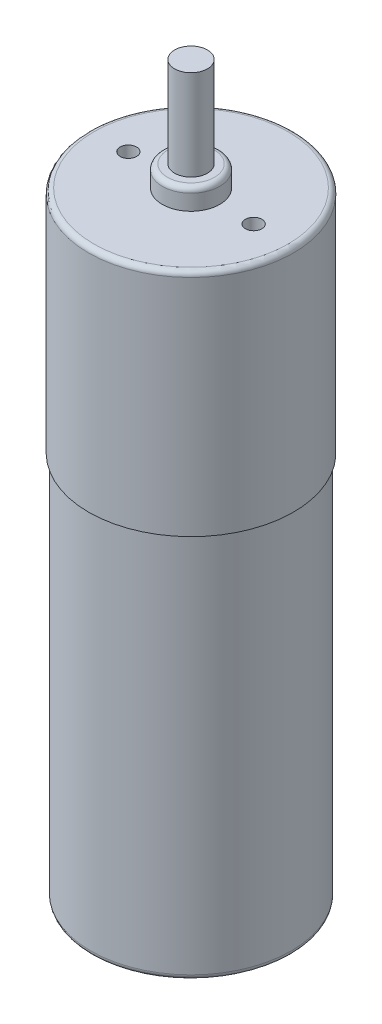
SolidWorks part; units mm, degrees
material "6061-T6 (SS)"
ref_plane "Front Plane" through (0, 0, 0) normal (0, 0, 1) x (1, 0, 0)
ref_plane "Top Plane" through (0, 0, 0) normal (0, 1, 0) x (1, 0, 0)
ref_plane "Right Plane" through (0, 0, 0) normal (1, 0, 0) x (0, 0, -1)
sketch "Sketch1" plane through (0, 0, 0) normal (0, 1, 0) x (1, 0, 0)
  circle A0 centre (0, 0) radius 12.192
  dimension "D1" = 24.384
extrude "Boss-Extrude1" add sketch "Sketch1" along normal blind 46.99
sketch "Sketch2" plane through (0, 46.99, 0) normal (0, 1, 0) x (1, 0, 0)
  circle A0 centre (0, 0) radius 12.4587
  dimension "D1" = 24.9174
extrude "Boss-Extrude2" add sketch "Sketch2" along normal blind 27.94
sketch "Sketch3" plane through (0, 74.93, 0) normal (0, 1, 0) x (1, 0, 0)
  circle A0 centre (0, 0) radius 3.4925
  dimension "D1" = 6.985
extrude "Boss-Extrude3" add sketch "Sketch3" along normal blind 2.54
sketch "Sketch4" plane through (0, 77.47, 0) normal (0, 1, 0) x (1, 0, 0)
  circle A0 centre (0, 0) radius 1.9939
  dimension "D1" = 3.9878
extrude "Boss-Extrude4" add sketch "Sketch4" along normal blind 10.9982
fillet "Fillet1" radius 0.635 2 edges at (0, 74.93, 12.4587) (0, 0, 12.192)
fillet "Fillet2" radius 0.635 1 edges at (0, 77.47, 3.4925)
sketch "Sketch5" plane through (0, 74.93, 0) normal (0, 1, 0) x (1, 0, 0)
  line L0 (-0.1693, 0) -> (7.9301, 0) construction
  line L1 (0, 0) -> (0, 50000) construction
  circle A0 centre (7.62, 0) radius 1.0033
  circle A1 centre (-7.62, 0) radius 1.0033
  dimension "D1" = 2.0066
  dimension "D2" = 7.62
extrude "Cut-Extrude1" cut sketch "Sketch5" against normal blind 12.7
